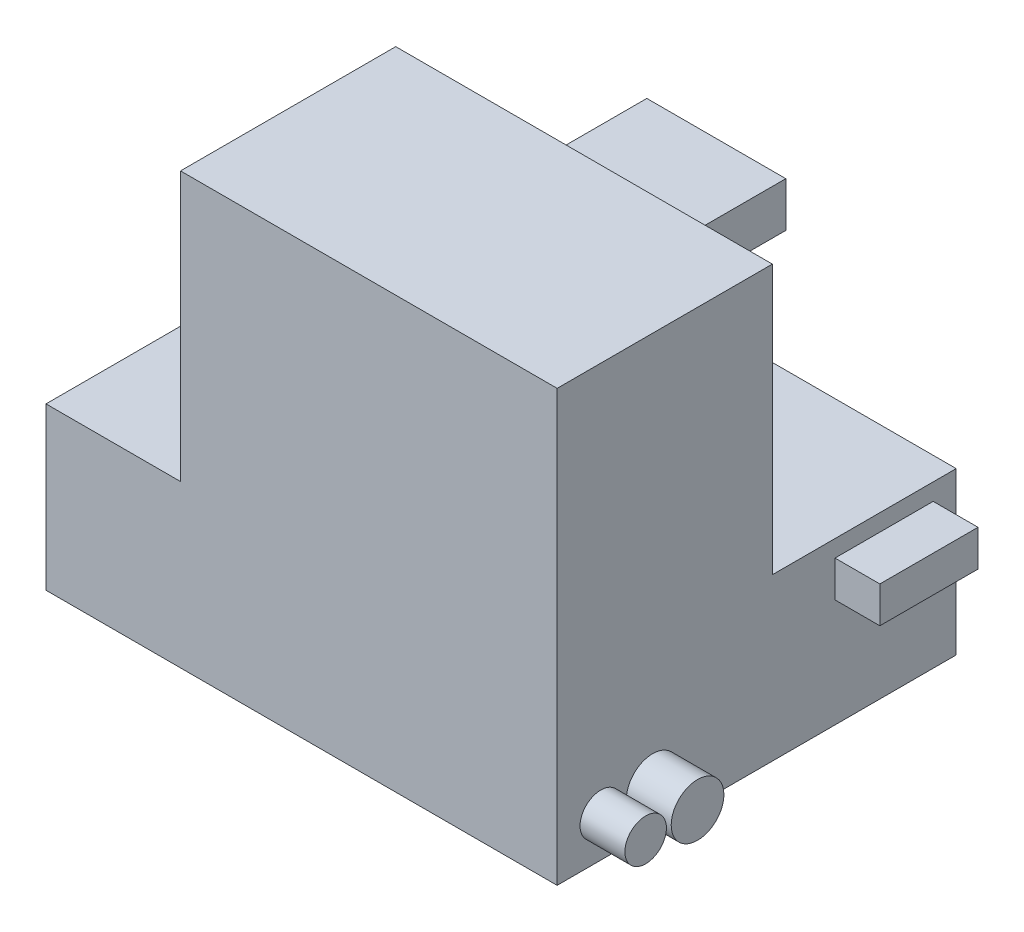
SolidWorks part; units mm, degrees
ref_plane "Front Plane" through (0, 0, 0) normal (0, 0, 1) x (1, 0, 0)
ref_plane "Top Plane" through (0, 0, 0) normal (0, 1, 0) x (1, 0, 0)
ref_plane "Right Plane" through (0, 0, 0) normal (1, 0, 0) x (0, 0, -1)
sketch "Sketch1" plane through (0, 0, 0) normal (0, 1, 0) x (1, 0, 0)
  line L1 (0, 0) -> (57, 0)
  line L2 (0, 0) -> (0, 44.5)
  line L3 (0, 44.5) -> (57, 44.5)
  line L4 (57, 0) -> (57, 44.5)
  dimension "D1" = 57
  dimension "D2" = 44.5
extrude "Boss-Extrude1" add sketch "Sketch1" along normal blind 18
sketch "Sketch2" plane through (57, 0, 0) normal (1, 0, 0) x (0, 0, -1)
  line L1 (30.9862, 16.1165) -> (41.9314, 16.1165)
  line L2 (30.9862, 16.1165) -> (30.9862, 12.0761)
  line L3 (30.9862, 12.0761) -> (41.9314, 12.0761)
  line L4 (41.9314, 16.1165) -> (41.9314, 12.0761)
  circle A0 centre (4.8699, 4.4583) radius 2.3146
  circle A1 centre (10.6563, 4.4583) radius 2.9373
extrude "Boss-Extrude2" add sketch "Sketch2" along normal blind 5
sketch "Sketch3" plane through (0, 18, 0) normal (0, 1, 0) x (1, 0, 0)
  line L0 (0, 0) -> (57, 0) construction
  line L1 (57, 0) -> (15, 0)
  line L2 (57, 0) -> (57, 24)
  line L3 (57, 24) -> (15, 24)
  line L4 (15, 0) -> (15, 24)
  line L5 (57, 0) -> (57, 44.5) construction
  dimension "D1" = 42
  dimension "D2" = 24
extrude "Boss-Extrude3" add sketch "Sketch3" along normal blind 30
sketch "Sketch4" plane through (0, 0, -44.5) normal (0, 0, -1) x (-1, 0, 0)
  line L0 (0, 18) -> (0, 0) construction
  line L1 (-18, 16.5) -> (-2.5, 16.5)
  line L2 (-18, 16.5) -> (-18, 11.5)
  line L3 (-18, 11.5) -> (-2.5, 11.5)
  line L4 (-2.5, 16.5) -> (-2.5, 11.5)
  line L5 (-57, 0) -> (0, 0) construction
  dimension "D1" = 5
  dimension "D2" = 15.5
  dimension "D3" = 2.5
  dimension "D4" = 11.5
extrude "Boss-Extrude4" add sketch "Sketch4" along normal blind 20
sketch "Sketch5" plane through (0, 0, 0) normal (0, -1, 0) x (1, 0, 0)
  line L0 (0, 0) -> (57, 0) construction
  line L1 (57, 0) -> (57, -44.5) construction
  circle A0 centre (3.66, -3.81) radius 1.7
  circle A1 centre (16.36, -40.64) radius 1.7
  circle A2 centre (53.19, -19.05) radius 1.7
  dimension "D3" = 40.64
  dimension "D4" = 40.64
  dimension "D7" = 3.4
  dimension "D1" = 19.05
  dimension "D2" = 3.81
  dimension "D5" = 53.34
  dimension "D6" = 3.81
extrude "Cut-Extrude1" cut sketch "Sketch5" against normal blind 10
